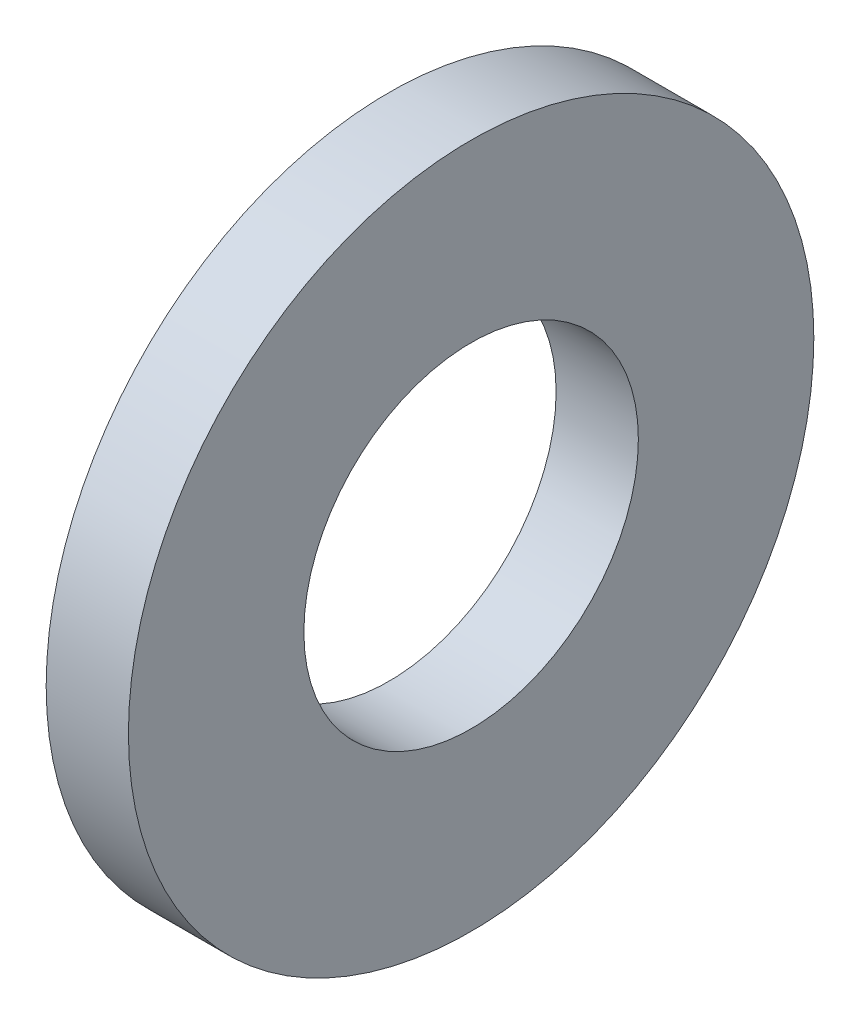
SolidWorks part; units mm, degrees
ref_plane "Plane1" through (0, 0, 0) normal (0, 0, 1) x (1, 0, 0)
ref_plane "Plane2" through (0, 0, 0) normal (0, 1, 0) x (1, 0, 0)
ref_plane "Plane3" through (0, 0, 0) normal (1, 0, 0) x (0, 0, -1)
sketch "Sketch1" plane through (0, 0, 0) normal (0, 0, 1) x (1, 0, 0)
  line L0 (-34.925, 0) -> (9.525, 0) construction
  line L1 (0, 2.44) -> (0, 5)
  line L2 (0, 5) -> (-1.2, 5)
  line L3 (-1.2, 5) -> (-1.2, 2.44)
  line L4 (-1.2, 2.44) -> (0, 2.44)
  dimension "Thickness" = 1.2
  dimension "Inside_dia" = 4.88
  dimension "Outside_dia" = 10
revolve "Base-Revolve" add sketch "Sketch1" angle 360 about L0
